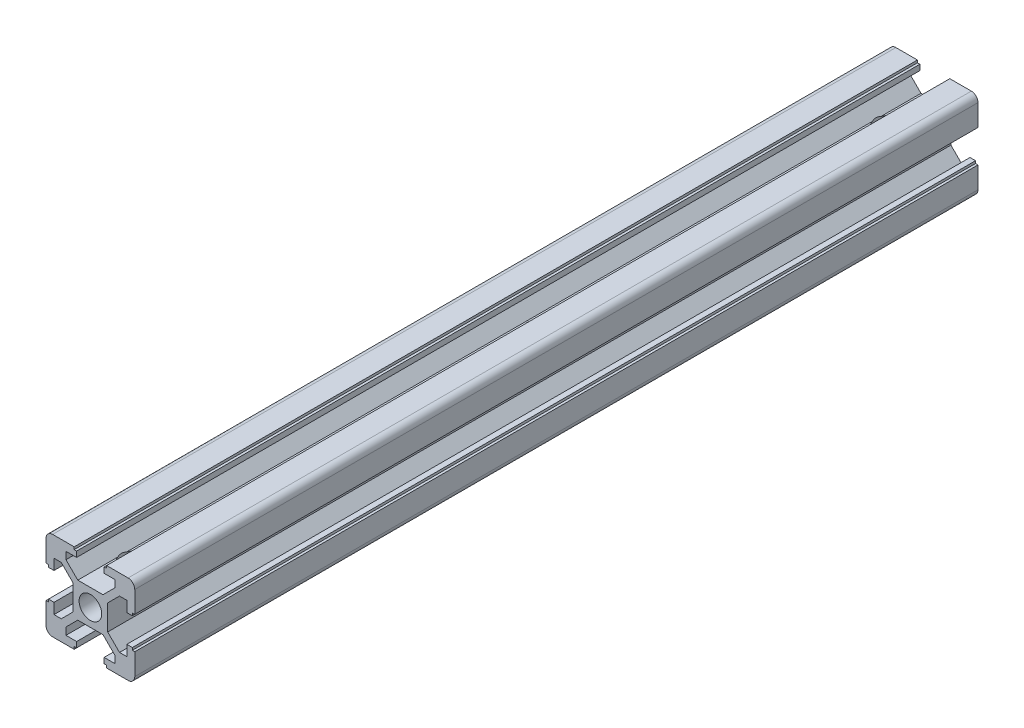
SolidWorks part; units mm, degrees
material "6063-T5"
ref_plane "前视基准面" through (0, 0, 0) normal (0, 0, 1) x (1, 0, 0)
ref_plane "上视基准面" through (0, 0, 0) normal (0, 1, 0) x (1, 0, 0)
ref_plane "右视基准面" through (0, 0, 0) normal (1, 0, 0) x (0, 0, -1)
sketch "草图2" plane through (0, 0, 0) normal (0, 0, 1) x (1, 0, 0)
  line L0 (-3.9, 2.8393) -> (-6.5607, 5.5)
  line L1 (-2.8393, 3.9) -> (2.8393, 3.9)
  line L2 (-3.9, 2.8393) -> (-3.9, -2.8393)
  line L3 (-2.8393, -3.9) -> (2.8393, -3.9)
  line L4 (3.9, 2.8393) -> (3.9, -2.8393)
  line L5 (-3.9, 3.9) -> (3.9, -3.9) construction
  line L6 (-3.9, -3.9) -> (3.9, 3.9) construction
  line L7 (-2.8393, 3.9) -> (-5.5, 6.5607)
  line L8 (-5.5, 6.5607) -> (-5.5, 8.2)
  line L9 (-5.5, 8.2) -> (-3.1, 8.2)
  line L10 (-3.1, 8.2) -> (-3.1, 9.45)
  line L11 (-3.1, 9.45) -> (-3.65, 9.45)
  line L12 (-3.65, 9.45) -> (-3.65, 10)
  line L13 (-3.65, 10) -> (-8.5, 10)
  line L14 (-6.5607, 5.5) -> (-8.2, 5.5)
  line L15 (-10, 3.65) -> (-10, 8.5)
  line L16 (-9.45, 3.65) -> (-10, 3.65)
  line L17 (-9.45, 3.1) -> (-9.45, 3.65)
  line L18 (-8.2, 3.1) -> (-9.45, 3.1)
  line L19 (-8.2, 5.5) -> (-8.2, 3.1)
  line L20 (2.8393, 3.9) -> (5.5, 6.5607)
  line L21 (3.9, 2.8393) -> (6.5607, 5.5)
  line L22 (6.5607, 5.5) -> (8.2, 5.5)
  line L23 (8.2, 5.5) -> (8.2, 3.1)
  line L24 (8.2, 3.1) -> (9.45, 3.1)
  line L25 (9.45, 3.1) -> (9.45, 3.65)
  line L26 (9.45, 3.65) -> (10, 3.65)
  line L27 (10, 3.65) -> (10, 8.5)
  line L28 (5.5, 6.5607) -> (5.5, 8.2)
  line L29 (3.65, 10) -> (8.5, 10)
  line L30 (3.65, 9.45) -> (3.65, 10)
  line L31 (3.1, 9.45) -> (3.65, 9.45)
  line L32 (3.1, 8.2) -> (3.1, 9.45)
  line L33 (5.5, 8.2) -> (3.1, 8.2)
  line L34 (3.9, -2.8393) -> (6.5607, -5.5)
  line L35 (2.8393, -3.9) -> (5.5, -6.5607)
  line L36 (5.5, -6.5607) -> (5.5, -8.2)
  line L37 (5.5, -8.2) -> (3.1, -8.2)
  line L38 (3.1, -8.2) -> (3.1, -9.45)
  line L39 (3.1, -9.45) -> (3.65, -9.45)
  line L40 (3.65, -9.45) -> (3.65, -10)
  line L41 (3.65, -10) -> (8.5, -10)
  line L42 (6.5607, -5.5) -> (8.2, -5.5)
  line L43 (10, -3.65) -> (10, -8.5)
  line L44 (9.45, -3.65) -> (10, -3.65)
  line L45 (9.45, -3.1) -> (9.45, -3.65)
  line L46 (8.2, -3.1) -> (9.45, -3.1)
  line L47 (8.2, -5.5) -> (8.2, -3.1)
  line L48 (-2.8393, -3.9) -> (-5.5, -6.5607)
  line L49 (-3.9, -2.8393) -> (-6.5607, -5.5)
  line L50 (-6.5607, -5.5) -> (-8.2, -5.5)
  line L51 (-8.2, -5.5) -> (-8.2, -3.1)
  line L52 (-8.2, -3.1) -> (-9.45, -3.1)
  line L53 (-9.45, -3.1) -> (-9.45, -3.65)
  line L54 (-9.45, -3.65) -> (-10, -3.65)
  line L55 (-10, -3.65) -> (-10, -8.5)
  line L56 (-5.5, -6.5607) -> (-5.5, -8.2)
  line L57 (-3.65, -10) -> (-8.5, -10)
  line L58 (-3.65, -9.45) -> (-3.65, -10)
  line L59 (-3.1, -9.45) -> (-3.65, -9.45)
  line L60 (-3.1, -8.2) -> (-3.1, -9.45)
  line L61 (-5.5, -8.2) -> (-3.1, -8.2)
  circle A0 centre (0, 0) radius 2.55
  arc A1 (-8.5, 10) -> (-10, 8.5) centre (-8.5, 8.5) ccw
  arc A2 (10, 8.5) -> (8.5, 10) centre (8.5, 8.5) ccw
  arc A3 (8.5, -10) -> (10, -8.5) centre (8.5, -8.5) ccw
  arc A4 (-10, -8.5) -> (-8.5, -10) centre (-8.5, -8.5) ccw
  point P25 (-10, 10)
  point P79 (0, 0)
  dimension "D1" = 5.1
  dimension "D9" = 1.5
  dimension "D2" = 7.8
  dimension "D3" = 1.5
  dimension "D4" = 10
  dimension "D5" = 3.1
  dimension "D6" = 0.55
  dimension "D7" = 1.8
  dimension "D8" = 5.5
  dimension "D11" = 3.9
  dimension "D10" = 4
extrude "凸台-拉伸1" add sketch "草图2" along normal blind 190
sketch "草图3" plane through (0, -10, 0) normal (0, -1, 0) x (1, 0, 0)
  line L1 (-8.5, 0) -> (-3.65, 0) construction
  line L2 (0, 0) -> (0, 10) construction
  circle A0 centre (0, 10) radius 3
  dimension "D1" = 6
  dimension "D2" = 10
extrude "切除-拉伸1" cut sketch "草图3" against normal through all
sketch "草图4" plane through (0, 10, 0) normal (0, 1, 0) x (1, 0, 0)
  circle A0 centre (0, -48) radius 2.5
  circle A1 centre (0, -89) radius 2.5
  dimension "D1" = 5
  dimension "D2" = 5
extrude "切除-拉伸2" cut sketch "草图4" against normal through all
sketch "草图5" plane through (0, 10, 0) normal (0, 1, 0) x (1, 0, 0)
  line L0 (2.8393, -190) -> (-2.8393, -190) construction
  line L1 (0, -180) -> (0, -190) construction
  circle A0 centre (0, -180) radius 3
  dimension "D1" = 6
  dimension "D2" = 10
extrude "切除-拉伸3" cut sketch "草图5" against normal through all
